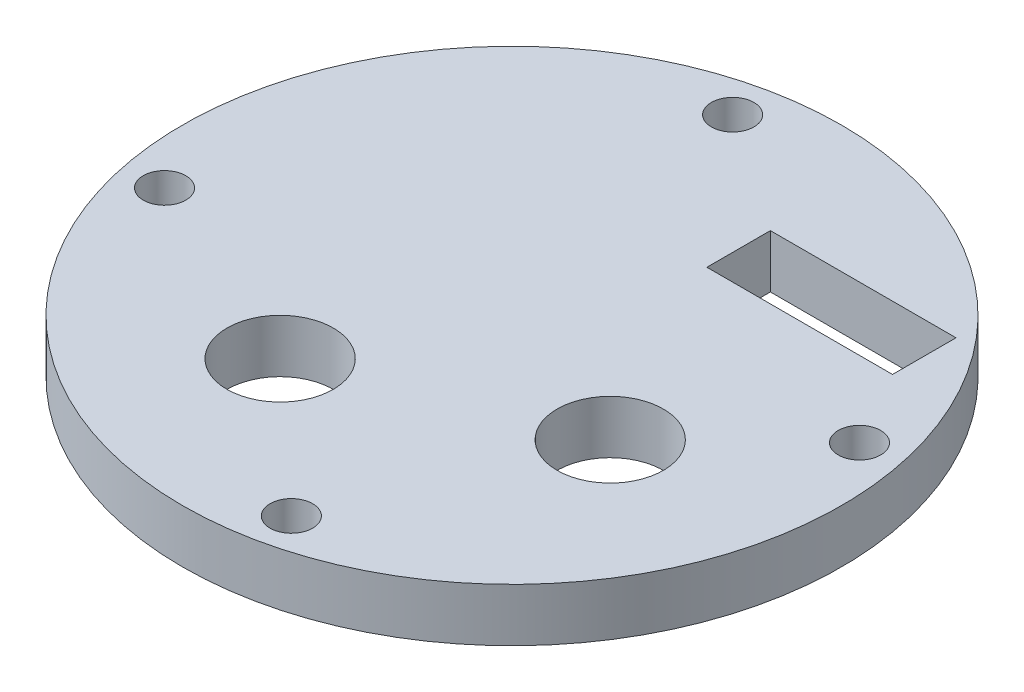
SolidWorks part; units mm, degrees
ref_plane "Front Plane" through (0, 0, 0) normal (0, 0, 1) x (1, 0, 0)
ref_plane "Top Plane" through (0, 0, 0) normal (0, 1, 0) x (1, 0, 0)
ref_plane "Right Plane" through (0, 0, 0) normal (1, 0, 0) x (0, 0, -1)
sketch "Sketch1" plane through (0, 0, 0) normal (0, 1, 0) x (1, 0, 0)
  circle A0 centre (0, 0) radius 31
  dimension "D1" = 62
extrude "Boss-Extrude1" add sketch "Sketch1" along normal blind 5
sketch "Sketch2" plane through (0, 5, 0) normal (0, 1, 0) x (1, 0, 0)
  circle A0 centre (-26.72, -5.9654) radius 2
  circle A1 centre (-5.9654, 26.72) radius 2
  circle A2 centre (26.72, 5.9654) radius 2
  circle A3 centre (5.9654, -26.72) radius 2
  point P11 (0, 0)
  dimension "D1" = 4
extrude "Cut-Extrude1" cut sketch "Sketch2" against normal blind 12.5
sketch "Sketch5" plane through (0, 5, 0) normal (0, 1, 0) x (1, 0, 0)
  line L1 (22.7143, 19.0522) -> (5.2523, 19.0522)
  line L2 (22.7143, 19.0522) -> (22.7143, 13.0809)
  line L3 (22.7143, 13.0809) -> (5.2523, 13.0809)
  line L4 (5.2523, 19.0522) -> (5.2523, 13.0809)
extrude "Cut-Extrude3" cut sketch "Sketch5" against normal blind 5
sketch "Sketch6" plane through (0, 5, 0) normal (0, 1, 0) x (1, 0, 0)
  circle A0 centre (-7.3724, -14.4384) radius 5
  circle A1 centre (14.7535, -5.5129) radius 5
extrude "Cut-Extrude4" cut sketch "Sketch6" against normal blind 5
